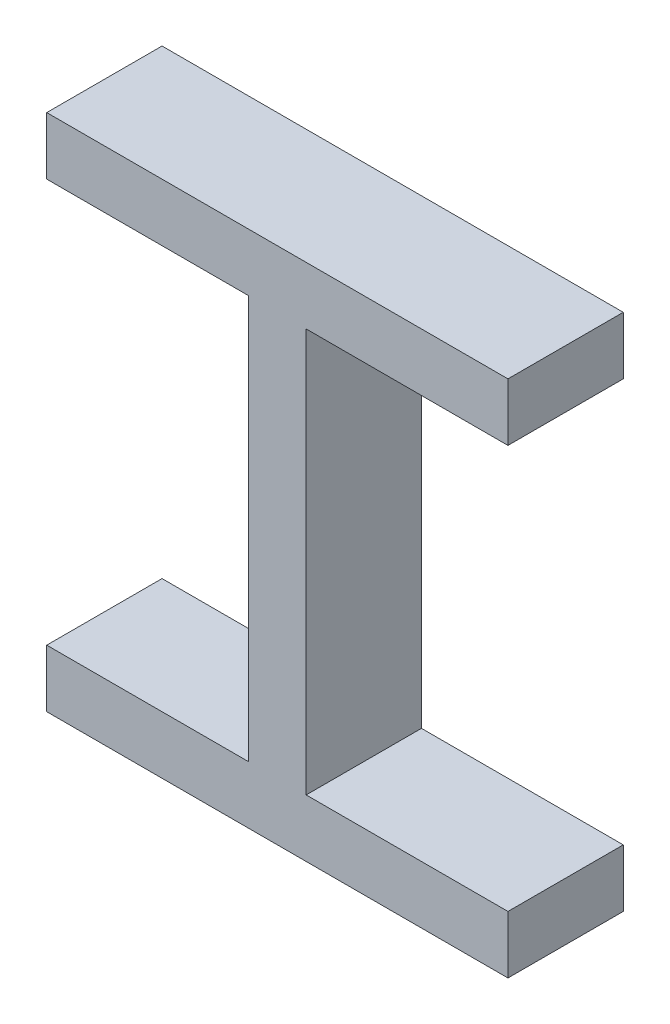
SolidWorks part; units mm, degrees
ref_plane "Front Plane" through (0, 0, 0) normal (0, 0, 1) x (1, 0, 0)
ref_plane "Top Plane" through (0, 0, 0) normal (0, 1, 0) x (1, 0, 0)
ref_plane "Right Plane" through (0, 0, 0) normal (1, 0, 0) x (0, 0, -1)
sketch "Sketch1" plane through (0, 0, 0) normal (0, 0, 1) x (1, 0, 0)
  line L0 (90, -20) -> (160, -20)
  line L1 (0, 0) -> (160, 0)
  line L2 (0, 0) -> (0, -20)
  line L3 (0, -20) -> (70, -20)
  line L4 (160, 0) -> (160, -20)
  line L6 (70, -20) -> (70, -160)
  line L8 (90, -20) -> (90, -160)
  line L9 (0, -160) -> (70, -160)
  line L10 (0, -160) -> (0, -180)
  line L11 (0, -180) -> (160, -180)
  line L12 (160, -160) -> (160, -180)
  line L13 (90, -160) -> (160, -160)
  dimension "D1" = 20
  dimension "D2" = 20
  dimension "D3" = 20
  dimension "D4" = 140
  dimension "D5" = 160
  dimension "D6" = 160
  dimension "D7" = 70
extrude "Boss-Extrude1" add sketch "Sketch1" along normal blind 40
